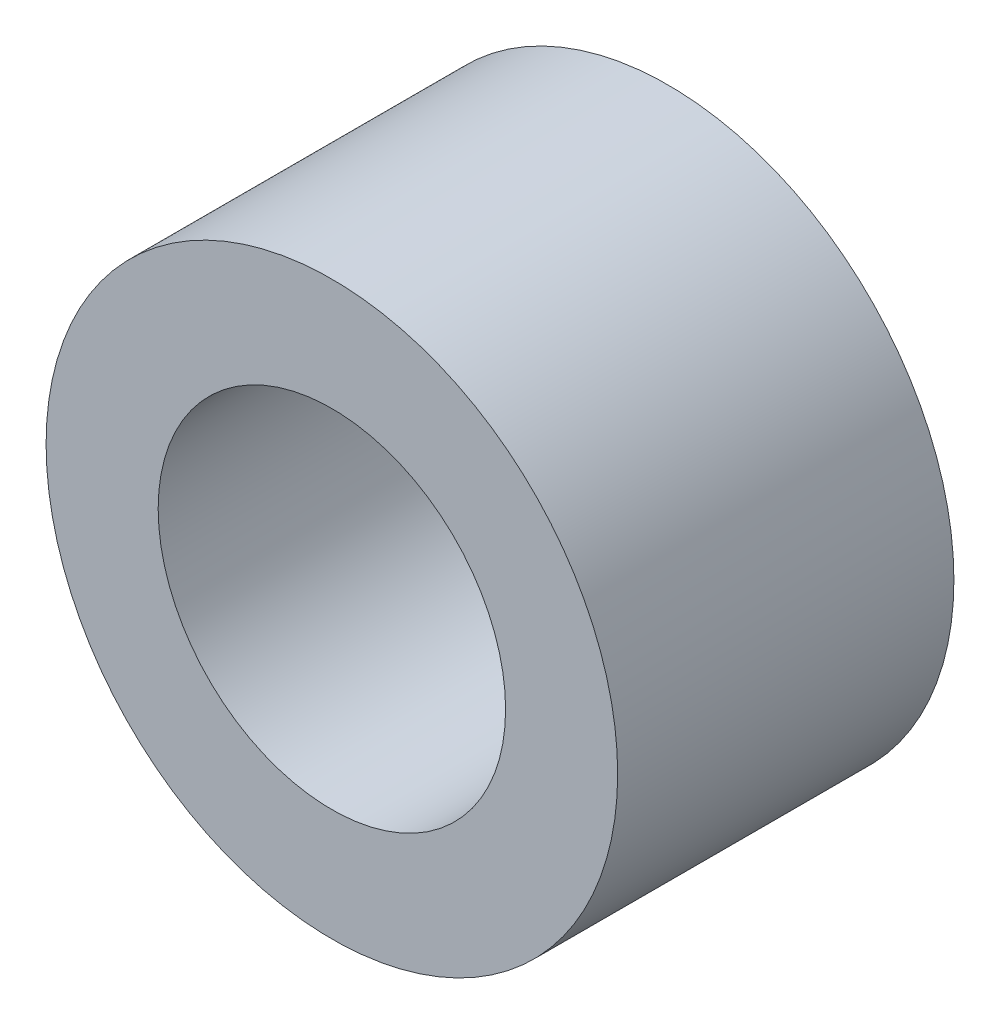
SolidWorks part; units mm, degrees
ref_plane "前视基准面" through (0, 0, 0) normal (0, 0, 1) x (1, 0, 0)
ref_plane "上视基准面" through (0, 0, 0) normal (0, 1, 0) x (1, 0, 0)
ref_plane "右视基准面" through (0, 0, 0) normal (1, 0, 0) x (0, 0, -1)
sketch "草图1" plane through (0, 0, 0) normal (0, 0, 1) x (1, 0, 0)
  circle A0 centre (0, 0) radius 1.55
  circle A1 centre (0, 0) radius 2.55
  dimension "D1" = 3.1
  dimension "D2" = 1
extrude "凸台-拉伸1" add sketch "草图1" along normal mid plane 3
